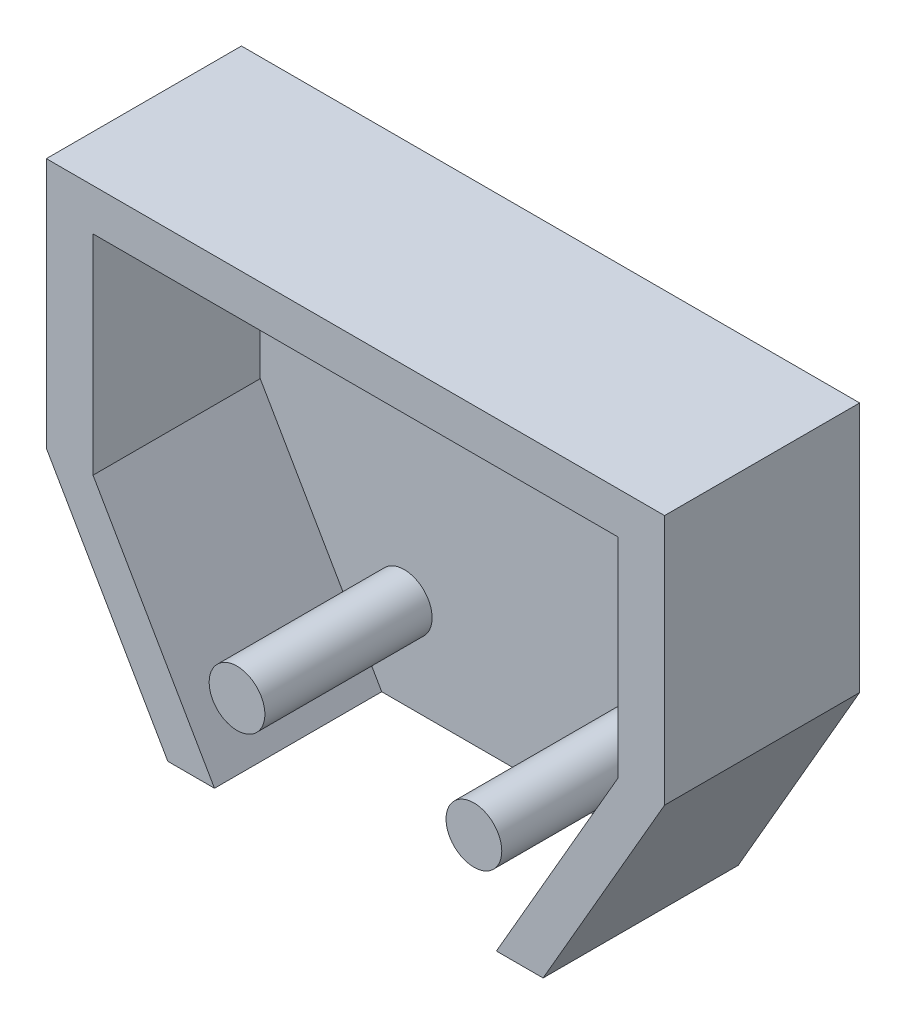
SolidWorks part; units mm, degrees
ref_plane "정면" through (0, 0, 0) normal (0, 0, 1) x (1, 0, 0)
ref_plane "윗면" through (0, 0, 0) normal (0, 1, 0) x (1, 0, 0)
ref_plane "우측면" through (0, 0, 0) normal (1, 0, 0) x (0, 0, -1)
sketch "스케치2" plane through (0, 0, 0) normal (0, 0, 1) x (1, 0, 0)
  line L0 (0, 0) -> (47.71, 0)
  line L1 (47.71, 0) -> (37.32, -17.996)
  line L2 (37.32, -17.996) -> (10.39, -17.996)
  line L3 (10.39, -17.996) -> (0, 0)
  dimension "D1" = 60
  dimension "D2" = 47.71
  dimension "D3" = 20.78
extrude "보스-돌출1" add sketch "스케치2" along normal blind 2
sketch "스케치3" plane through (0, 0, 2) normal (0, 0, 1) x (1, 0, 0)
  line L0 (23.855, 0) -> (23.855, -17.996)
  line L1 (47.71, 0) -> (0, 0) construction
  line L2 (10.39, -17.996) -> (37.32, -17.996) construction
  line L3 (23.855, -17.996) -> (23.855, -2.996)
  line L4 (42.5153, -2.996) -> (5.1947, -2.996)
  line L5 (5.1947, -2.996) -> (13.855, -17.996)
  line L6 (13.855, -17.996) -> (33.855, -17.996)
  line L7 (17.0871, -10.5941) -> (19.0871, -14.0582)
  line L8 (13.6229, -12.5941) -> (15.6229, -16.0582)
  line L9 (15.355, -4.996) -> (17.355, -4.996)
  line L10 (17.355, -8.996) -> (15.355, -8.996)
  line L11 (30.355, -8.996) -> (32.355, -8.996)
  line L12 (32.355, -4.996) -> (30.355, -4.996)
  line L13 (34.0871, -12.5941) -> (32.0871, -16.0582)
  line L14 (30.6229, -10.5941) -> (28.6229, -14.0582)
  line L15 (42.5153, -2.996) -> (33.855, -17.996)
  line L16 (33.855, -17.996) -> (37.32, -17.996)
  line L17 (37.32, -17.996) -> (47.71, 0)
  line L18 (47.71, 0) -> (0, 0)
  line L19 (0, 0) -> (10.39, -17.996)
  line L20 (10.39, -17.996) -> (13.855, -17.996)
  circle A0 centre (17.355, -15.0582) radius 2
  circle A1 centre (15.355, -11.5941) radius 2
  circle A2 centre (15.355, -6.996) radius 2
  circle A3 centre (17.355, -6.996) radius 2
  circle A4 centre (30.355, -6.996) radius 2
  circle A5 centre (32.355, -6.996) radius 2
  circle A6 centre (32.355, -11.5941) radius 2
  circle A7 centre (30.355, -15.0582) radius 2
  line M4 (47.71, 0) -> (0, 0)
  dimension "D4" = 4
  dimension "D8" = 4
  dimension "D1" = 15
  dimension "D2" = 60
  dimension "D3" = 10
  dimension "D5" = 2
  dimension "D6" = 2.5
  dimension "D7" = 6.5
  dimension "D9" = 2
  dimension "D11" = 2
sketch "스케치4" plane through (0, 0, 2) normal (0, 0, 1) x (1, 0, 0)
  line L0 (23.855, 2.0529) -> (23.855, -17.996)
  line L1 (23.855, -17.996) -> (23.855, -2.996)
  line L2 (42.5153, -2.996) -> (5.1947, -2.996)
  line L3 (5.1947, -2.996) -> (13.855, -17.996)
  line L4 (13.855, -17.996) -> (33.855, -17.996)
  line L5 (18.221, -12.5582) -> (19.0871, -14.0582)
  line L6 (14.7569, -14.5582) -> (15.6229, -16.0582)
  line L7 (15.855, -4.996) -> (16.855, -4.996)
  line L8 (16.855, -8.996) -> (15.855, -8.996)
  line L9 (30.855, -8.996) -> (31.855, -8.996)
  line L10 (31.855, -4.996) -> (30.855, -4.996)
  line L11 (32.9531, -14.5582) -> (32.0871, -16.0582)
  line L12 (29.489, -12.5582) -> (28.6229, -14.0582)
  line L13 (42.5153, -2.996) -> (33.855, -17.996)
  line L14 (33.855, -17.996) -> (37.32, -17.996)
  line L15 (37.32, -17.996) -> (47.71, 0)
  line L16 (47.71, 0) -> (0, 0)
  line L17 (0, 0) -> (10.39, -17.996)
  line L18 (10.39, -17.996) -> (13.855, -17.996)
  line L19 (10.39, -17.996) -> (0, 0)
  line L20 (47.71, 0) -> (37.32, -17.996)
  line L21 (13.7395, -17.996) -> (5.0215, -2.896)
  line L22 (5.0215, -2.896) -> (42.6885, -2.896)
  line L23 (42.6885, -2.896) -> (33.9705, -17.996)
  line L24 (42.6885, -2.896) -> (46.038, -2.896)
  line L25 (5.0215, -2.896) -> (1.672, -2.896)
  circle A0 centre (17.355, -15.0582) radius 2
  circle A1 centre (16.489, -13.5582) radius 2
  circle A2 centre (15.855, -6.996) radius 2
  circle A3 centre (16.855, -6.996) radius 2
  circle A4 centre (30.855, -6.996) radius 2
  circle A5 centre (31.855, -6.996) radius 2
  circle A6 centre (31.221, -13.5582) radius 2
  circle A7 centre (30.355, -15.0582) radius 2
  point P47 (10.39, -17.996)
  line M10 (10.39, -17.996) -> (37.32, -17.996)
  line M11 (37.32, -17.996) -> (47.71, 0)
  dimension "D4" = 4
  dimension "D8" = 4
  dimension "D1" = 15
  dimension "D2" = 60
  dimension "D3" = 10
  dimension "D5" = 1.7321
  dimension "D6" = 2.5
  dimension "D7" = 6.5
  dimension "D9" = 1
  dimension "D10" = 7
  dimension "D11" = 2
  dimension "D12" = 47.71
  dimension "D13" = 3.0008
  dimension "D14" = 2.996
  dimension "D15" = 0.1
  dimension "D16" = 0.1
  dimension "D17" = 0.1
extrude "보스-돌출5" add sketch "스케치4" along normal blind 12 contours L21 L25 L19 M10 | L24 L23 L14 M11
extrude "보스-돌출6" add sketch "스케치3" along normal blind 12 contours A1 | A6 M4
sketch "스케치5" plane through (0, 0, 2) normal (0, 0, 1) x (1, 0, 0)
  line L0 (0, 0) -> (47.71, 0)
  line L1 (47.71, 0) -> (46.038, -2.896)
  line L2 (46.038, -2.896) -> (1.672, -2.896)
  line L3 (1.672, -2.896) -> (0, 0)
extrude "컷-돌출1" cut sketch "스케치5" against normal blind 12
sketch "스케치6" plane through (0, -2.896, 0) normal (0, 1, 0) x (1, 0, 0)
  line L0 (5.0215, -14) -> (1.672, -14)
  line L1 (1.672, -14) -> (1.672, 0)
  line L2 (1.672, 0) -> (46.038, 0)
  line L3 (46.038, 0) -> (46.038, -14)
  line L4 (46.038, -14) -> (42.6885, -14)
  line L5 (42.6885, -14) -> (42.6885, -2)
  line L6 (42.6885, -14) -> (42.6885, -2) construction
  line L7 (42.6885, -2) -> (5.0215, -2)
  line L8 (5.0215, -2) -> (5.0215, -14)
extrude "보스-돌출7" add sketch "스케치6" along normal blind 15
sketch "스케치7" plane through (0, 12.104, 0) normal (0, 1, 0) x (1, 0, 0)
  line L1 (1.672, -14) -> (46.038, -14)
  line L2 (1.672, -14) -> (1.672, 0)
  line L3 (1.672, 0) -> (46.038, 0)
  line L4 (46.038, -14) -> (46.038, 0)
extrude "보스-돌출8" add sketch "스케치7" along normal blind 3
sketch "스케치9" plane through (0, 12.104, 0) normal (0, -1, 0) x (1, 0, 0)
  line L1 (5.195, 13) -> (42.515, 13)
  line L2 (5.195, 13) -> (5.195, 3)
  line L3 (5.195, 3) -> (42.515, 3)
  line L4 (42.515, 13) -> (42.515, 3)
  line L5 (23.855, 14) -> (23.855, 0) construction
  line L7 (5.0215, 14) -> (42.6885, 14) construction
  line L12 (42.6885, 14) -> (5.0215, 14)
  line L14 (10.39, 0) -> (37.32, 0) construction
  point P8 (23.855, 14)
  point P9 (23.855, 13)
  dimension "D1" = 10
  dimension "D2" = 37.32
  dimension "D3" = 1
extrude "컷-돌출3" cut sketch "스케치9" against normal blind 1 contours L5 L1 L2 L3 | L1 L5 L3 L4
